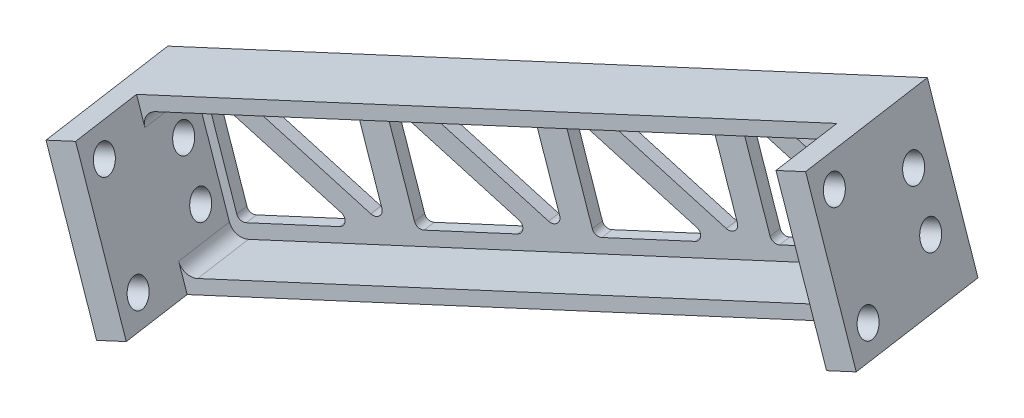
SolidWorks part; units mm, degrees
ref_plane "Front Plane" through (0, 0, 0) normal (0, 0, 1) x (1, 0, 0)
ref_plane "Top Plane" through (0, 0, 0) normal (0, 1, 0) x (1, 0, 0)
ref_plane "Right Plane" through (0, 0, 0) normal (1, 0, 0) x (0, 0, -1)
sketch3d "3DSketch1"
  line L0 (0, 0, 0) -> (-222.8841, -76.2, 50.8) construction
  line L1 (0, 0, 0) -> (-222.8841, 0, 50.8) construction
  line L2 (-222.8841, 0, 50.8) -> (-222.8841, -76.2, 50.8) construction
  line L3 (-222.8841, -76.2, 50.8) -> (-222.8841, -76.2, 0) construction
  line L4 (0, 0, 0) -> (-222.8841, -76.2, 0) construction
  line L5 (-193.5165, -66.1598, 44.1065) -> (-150.5903, -51.4841, 34.3227)
  line L6 (-150.5903, -51.4841, 34.3227) -> (0, 0, 0)
  line L7 (-193.5165, -66.1598, 44.1065) -> (-222.8841, -76.2, 50.8)
  dimension "D1" = 228.6
  dimension "D2" = 76.2
  dimension "D3" = 50.8
  dimension "D4" = 31.75
ref_plane "Plane1" through (0, 0, 0) normal (-0.925, -0.3162, 0.2108) x (0.1995, 0.0682, 0.9775)
ref_plane "Plane2" through (-222.8841, -76.2, 50.8) normal (-0.925, -0.3162, 0.2108) x (0.1995, 0.0682, 0.9775)
sketch "Sketch2" plane through (0, 0, 0) normal (-0.925, -0.3162, 0.2108) x (0.1995, 0.0682, 0.9775)
  line L1 (19.05, -19.05) -> (-19.05, -19.05)
  line L2 (19.05, -19.05) -> (19.05, 19.05)
  line L3 (19.05, 19.05) -> (-19.05, 19.05)
  line L4 (-19.05, -19.05) -> (-19.05, 19.05)
  line L5 (19.05, -19.05) -> (-19.05, 19.05) construction
  line L6 (19.05, 19.05) -> (-19.05, -19.05) construction
  point P0 (0, 0)
  dimension "D1" = 38.1
extrude "Boss-Extrude1" add sketch "Sketch2" along normal blind 6.35
sketch "Sketch3" plane through (-5.8735, -2.008, 1.3387) normal (-0.925, -0.3162, 0.2108) x (0.1995, 0.0682, 0.9775)
  line L0 (-15.875, -15.875) -> (0, -15.875)
  line L1 (-19.05, 19.05) -> (0, 19.05)
  line L2 (-19.05, 19.05) -> (-19.05, -19.05)
  line L3 (-19.05, -19.05) -> (0, -19.05)
  line L4 (0, 19.05) -> (0, 15.875)
  line L5 (-19.05, 19.05) -> (0, -19.05) construction
  line L6 (-19.05, -19.05) -> (0, 19.05) construction
  line L7 (-15.875, 15.875) -> (-15.875, -15.875)
  line L8 (-15.875, 15.875) -> (0, 15.875)
  line L9 (0, -15.875) -> (0, -19.05)
  line L10 (-19.05, 19.05) -> (-19.05, -19.05) construction
  line L11 (19.05, 19.05) -> (-19.05, 19.05) construction
  point P0 (-9.525, 0)
  dimension "D1" = 38.1
  dimension "D2" = 19.05
  dimension "D3" = 3.175
extrude "Boss-Extrude2" add sketch "Sketch3" along normal up to vertex (156.457 mm away)
sketch "Sketch4" plane through (-150.5903, -51.4841, 34.3227) normal (-0.925, -0.3162, 0.2108) x (0.1995, 0.0682, 0.9775)
  line L1 (-19.05, 19.05) -> (19.05, 19.05)
  line L2 (-19.05, 19.05) -> (-19.05, -19.05)
  line L3 (-19.05, -19.05) -> (19.05, -19.05)
  line L4 (19.05, 19.05) -> (19.05, -19.05)
  line L5 (-19.05, 19.05) -> (19.05, -19.05) construction
  line L6 (-19.05, -19.05) -> (19.05, 19.05) construction
  point P0 (0, 0)
  dimension "D1" = 38.1
extrude "Boss-Extrude3" add sketch "Sketch4" against normal blind 6.35
fillet "Fillet1" radius 3.175 4 edges at (-12.5924, 12.472, -6.4204) (-2.3214, -17.5708, -6.4204) (-151.4358, -34.996, 25.2249) (-141.1647, -65.0388, 25.2249)
hole_wizard "1/4 (0.25) Diameter Hole1" positions "Sketch6" profile "Sketch7" hole size "1/4" standard "ANSI Inch" end condition up to next
sketch "Sketch6" plane through (-144.7168, -49.476, 32.984) normal (0.925, 0.3162, -0.2108) x (-0.1995, -0.0682, -0.9775)
  line L0 (0, -19.05) -> (-19.05, -19.05) construction
  line L1 (-19.05, -19.05) -> (-19.05, 19.05) construction
  line L2 (-19.05, 19.05) -> (0, 19.05) construction
  line L3 (15.875, -12.7) -> (15.875, 12.7) construction
  point P0 (9.525, -6.35)
  point P2 (-12.7, -12.7)
  point P4 (-12.7, 12.7)
  point P6 (9.4701, 6.35)
  dimension "D1" = 6.35
  dimension "D2" = 6.35
  dimension "D3" = 6.35
  dimension "D4" = 12.7
  dimension "D5" = 12.7
  dimension "D6" = 6.35
sketch "Sketch7" plane through (-144.5627, -56.1342, 23.6731) normal (-0.0803, 0.7048, 0.7048) x (-0.3715, 0.635, -0.6773)
  line L0 (0, 0) -> (0, 25.6035)
  line L1 (0, 25.6035) -> (3.175, 25.6035)
  line L2 (3.175, 25.6035) -> (3.175, 0)
  line L5 (3.175, 0) -> (0, 0)
  line L11 (0, -6.35) -> (0, 107.95) construction
  dimension "Thru Hole Dia." = 6.35
  dimension "Thru Hole Depth" = 25.6035
sketch "Sketch8" plane through (-144.7168, -49.476, 32.984) normal (0.925, 0.3162, -0.2108) x (-0.1995, -0.0682, -0.9775)
  circle A0 centre (9.4701, 6.35) radius 5.334 construction
  circle A1 centre (9.525, -6.35) radius 5.334 construction
  circle A2 centre (-12.7, -12.7) radius 5.334 construction
  circle A3 centre (-12.7, 12.7) radius 5.334 construction
  dimension "D1" = 10.668
ref_plane "Plane3" through (-75.2952, -25.742, 17.1614) normal (0.925, 0.3162, -0.2108) x (-0.1995, -0.0682, -0.9775)
mirror "Mirror1" about plane through (-75.2952, -25.742, 17.1614) normal (0.925, 0.3162, -0.2108) of "1/4 (0.25) Diameter Hole1"
sketch "Sketch9" plane through (-3.1668, -1.0827, -15.5182) normal (0.1995, 0.0682, 0.9775) x (0.9799, -0.0139, -0.199)
  line L0 (-4.9846, -11.1375) -> (-11.5807, 7.7223)
  line L1 (-13.6032, 8.6967) -> (-32.463, 2.1007)
  line L2 (-32.6279, -0.828) -> (-7.1721, -13.0917)
  line L3 (-149.929, -35.6186) -> (-14.2318, 11.8404) construction
  line L4 (6.289, -17.9819) -> (-6.289, 17.9819) construction
  line L5 (-149.929, -35.6186) -> (-14.2318, 11.8404) construction
  line L6 (0.2951, -20.0783) -> (-12.283, 15.8856) construction
  line L7 (-38.6219, -2.9244) -> (-13.1661, -15.1881)
  line L8 (-13.331, -18.1168) -> (-32.1908, -24.7128)
  line L9 (-34.2134, -23.7384) -> (-40.8094, -4.8786)
  line L10 (-139.4472, -65.5885) -> (-3.7501, -18.1295) construction
  line L11 (-7.5415, -3.8268) -> (-37.5114, -14.3085) construction
  line L12 (-36.0807, 0.8354) -> (-42.0747, -1.261) construction
  arc A0 (-32.463, 2.1007) -> (-32.6279, -0.828) centre (-31.9389, 0.6022) ccw
  arc A1 (-11.5807, 7.7223) -> (-13.6032, 8.6967) centre (-13.0792, 7.1982) ccw
  arc A2 (-4.9846, -11.1375) -> (-7.1721, -13.0917) centre (-6.4831, -11.6615) cw
  arc A3 (-38.6219, -2.9244) -> (-40.8094, -4.8786) centre (-39.3109, -4.3546) ccw
  arc A4 (-32.1908, -24.7128) -> (-34.2134, -23.7384) centre (-32.7149, -23.2143) cw
  arc A5 (-13.331, -18.1168) -> (-13.1661, -15.1881) centre (-13.8551, -16.6183) ccw
  point P13 (-36.0807, 0.8354)
  point P16 (-12.1048, 9.2208)
  point P19 (-3.7194, -14.7551)
  point P29 (-33.6893, -25.2369)
  point P32 (-9.7133, -16.8515)
  dimension "D5" = 1.5875
  dimension "D9" = 1.5875
  dimension "D1" = 25.4
  dimension "D2" = 25.4
  dimension "D3" = 3.175
  dimension "D4" = 2.032
  dimension "D6" = 6.35
  dimension "D7" = 3.175
  dimension "D8" = 25.4
extrude "Cut-Extrude1" cut sketch "Sketch9" against normal up to next
pattern_linear "LPattern1" count 4 spacing 38.1 along (-0.925, -0.3162, 0.2108) of "Cut-Extrude1"
